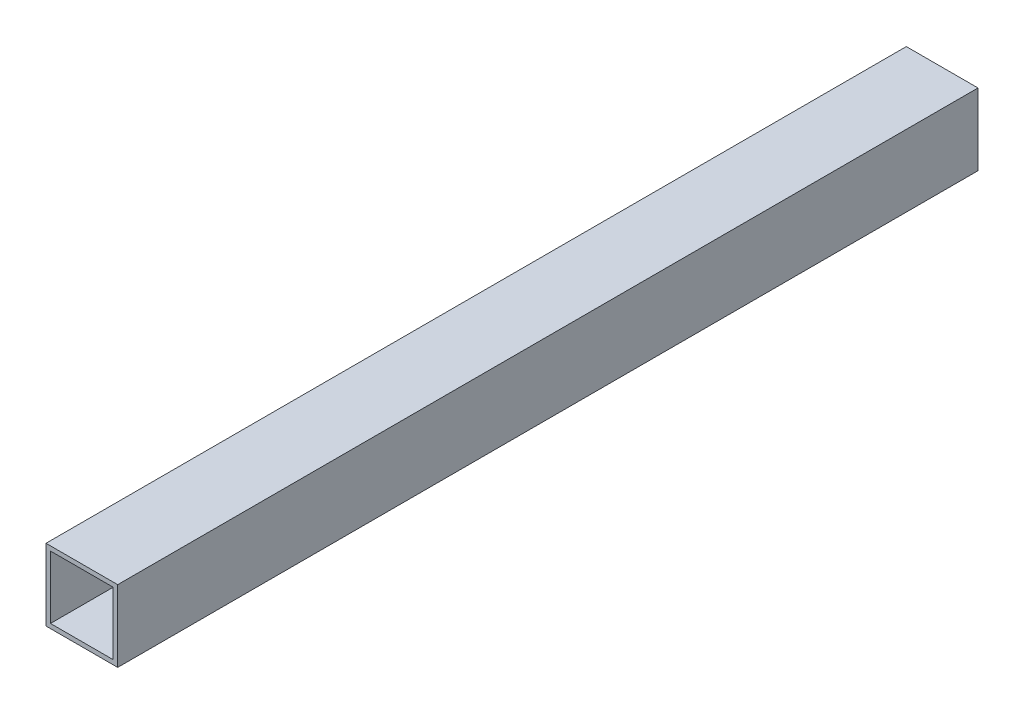
SolidWorks part; units mm, degrees
ref_plane "Front Plane" through (0, 0, 0) normal (0, 0, 1) x (1, 0, 0)
ref_plane "Top Plane" through (0, 0, 0) normal (0, 1, 0) x (1, 0, 0)
ref_plane "Right Plane" through (0, 0, 0) normal (1, 0, 0) x (0, 0, -1)
sketch "Sketch1" plane through (0, 0, 0) normal (0, 0, 1) x (1, 0, 0)
  line L1 (-11.1125, -11.1125) -> (11.1125, -11.1125)
  line L2 (-11.1125, -11.1125) -> (-11.1125, 11.1125)
  line L3 (-11.1125, 11.1125) -> (11.1125, 11.1125)
  line L4 (11.1125, -11.1125) -> (11.1125, 11.1125)
  line L5 (-11.1125, -11.1125) -> (11.1125, 11.1125) construction
  line L6 (-11.1125, 11.1125) -> (11.1125, -11.1125) construction
  line L7 (-12.7, -12.7) -> (12.7, -12.7)
  line L8 (-12.7, -12.7) -> (-12.7, 12.7)
  line L9 (-12.7, 12.7) -> (12.7, 12.7)
  line L10 (12.7, -12.7) -> (12.7, 12.7)
  line L11 (-12.7, -12.7) -> (12.7, 12.7) construction
  line L12 (-12.7, 12.7) -> (12.7, -12.7) construction
  point P0 (0, 0)
  point P6 (0, 0)
  dimension "D1" = 1.5875
  dimension "D2" = 25.4
extrude "Boss-Extrude1" add sketch "Sketch1" along normal blind 304.8
